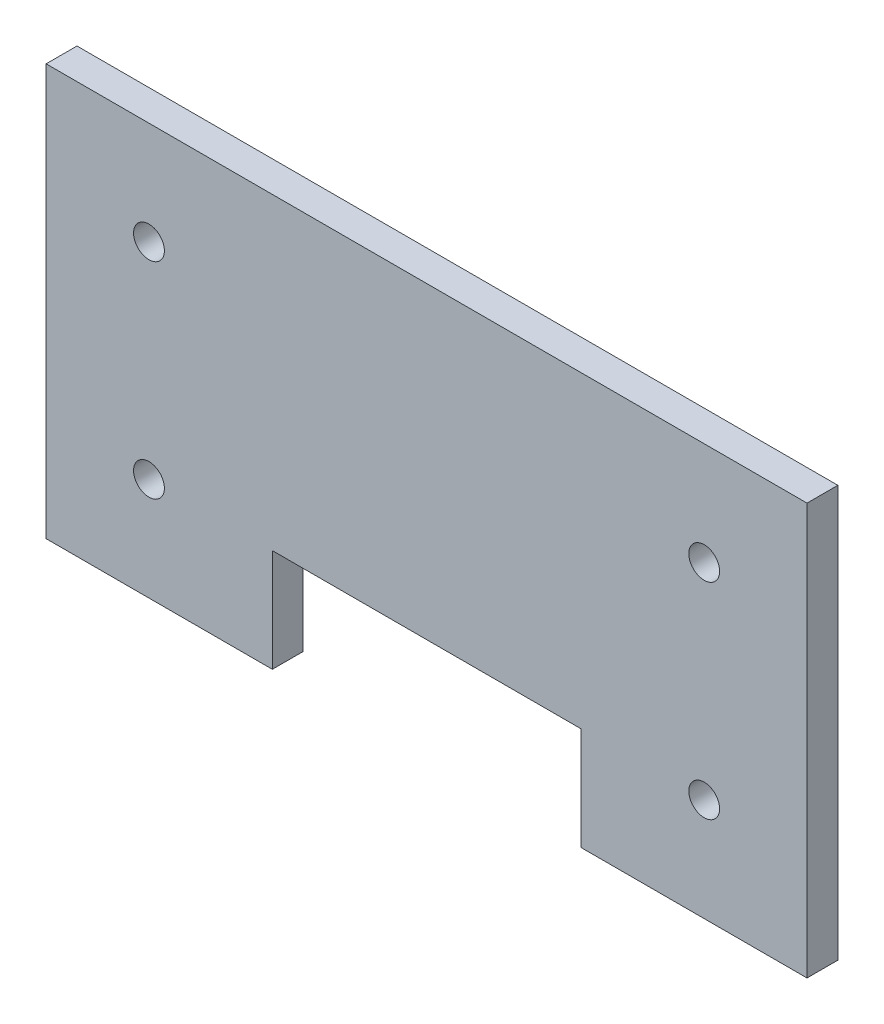
SolidWorks part; units mm, degrees
material "Thornel Mat VMA"
ref_plane "前视基准面" through (0, 0, 0) normal (0, 0, 1) x (1, 0, 0)
ref_plane "上视基准面" through (0, 0, 0) normal (0, 1, 0) x (1, 0, 0)
ref_plane "右视基准面" through (0, 0, 0) normal (1, 0, 0) x (0, 0, -1)
sketch "草图1" plane through (0, 0, 0) normal (0, 0, 1) x (1, 0, 0)
  line L1 (-37, 20) -> (37, 20)
  line L2 (-37, 20) -> (-37, -20)
  line L3 (-37, -20) -> (37, -20)
  line L4 (37, 20) -> (37, -20)
  line L5 (-37, 20) -> (37, -20) construction
  line L6 (-37, -20) -> (37, 20) construction
  line L7 (-27, 10) -> (27, 10) construction
  line L8 (-27, 10) -> (-27, -10) construction
  line L9 (-27, -10) -> (27, -10) construction
  line L10 (27, 10) -> (27, -10) construction
  line L11 (-27, 10) -> (27, -10) construction
  line L12 (-27, -10) -> (27, 10) construction
  line L13 (-15, -10) -> (15, -10)
  line L14 (-15, -10) -> (-15, -30)
  line L15 (-15, -30) -> (15, -30)
  line L16 (15, -10) -> (15, -30)
  line L17 (-15, -10) -> (15, -30) construction
  line L18 (-15, -30) -> (15, -10) construction
  circle A0 centre (-27, 10) radius 1.5
  circle A1 centre (-27, -10) radius 1.5
  circle A2 centre (27, 10) radius 1.5
  circle A3 centre (27, -10) radius 1.5
  point P0 (0, 0)
  point P6 (0, 0)
  point P15 (0, -20)
  dimension "D5" = 3
  dimension "D6" = 3
  dimension "D7" = 3
  dimension "D8" = 3
  dimension "D1" = 74
  dimension "D2" = 40
  dimension "D3" = 54
  dimension "D4" = 20
  dimension "D9" = 20
  dimension "D10" = 30
extrude "凸台-拉伸1" add sketch "草图1" along normal blind 3 contours L13 L16 L3 L4 L1 L2 L14 A3 A2 A1 A0
